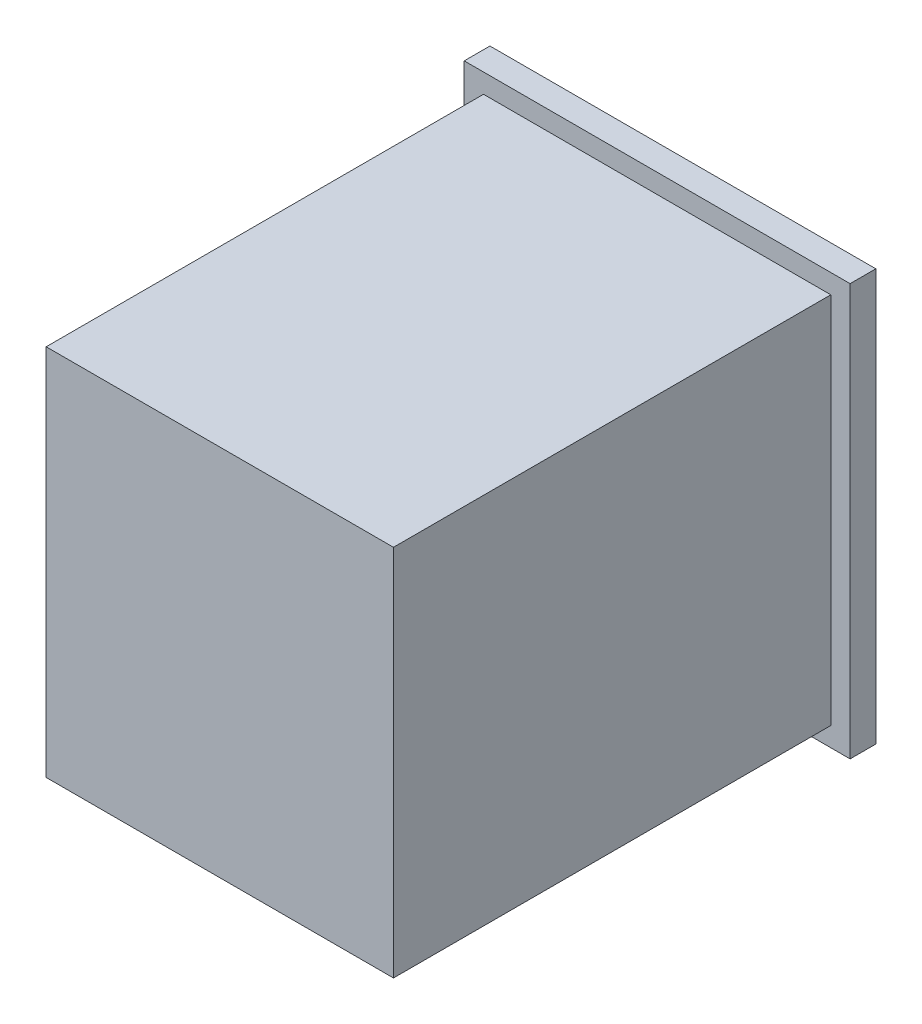
SolidWorks part; units mm, degrees
ref_plane "Front Plane" through (0, 0, 0) normal (0, 0, 1) x (1, 0, 0)
ref_plane "Top Plane" through (0, 0, 0) normal (0, 1, 0) x (1, 0, 0)
ref_plane "Right Plane" through (0, 0, 0) normal (1, 0, 0) x (0, 0, -1)
sketch "Sketch1" plane through (0, 0, 0) normal (0, 0, 1) x (1, 0, 0)
  line L1 (-6.75, -7.25) -> (6.75, -7.25)
  line L2 (-6.75, -7.25) -> (-6.75, 7.25)
  line L3 (-6.75, 7.25) -> (6.75, 7.25)
  line L4 (6.75, -7.25) -> (6.75, 7.25)
  line L5 (-6.75, -7.25) -> (6.75, 7.25) construction
  line L6 (-6.75, 7.25) -> (6.75, -7.25) construction
  point P0 (0, 0)
  dimension "D1" = 13.5
  dimension "D2" = 14.5
extrude "Boss-Extrude1" add sketch "Sketch1" along normal blind 17
sketch "Sketch2" plane through (0, 0, 0) normal (0, 0, 1) x (1, 0, 0)
  line L1 (7.5, -8) -> (-7.5, -8)
  line L2 (7.5, -8) -> (7.5, 8)
  line L3 (7.5, 8) -> (-7.5, 8)
  line L4 (-7.5, -8) -> (-7.5, 8)
  line L5 (7.5, -8) -> (-7.5, 8) construction
  line L6 (7.5, 8) -> (-7.5, -8) construction
  point P0 (0, 0)
  dimension "D1" = 15
  dimension "D2" = 16
extrude "Boss-Extrude2" add sketch "Sketch2" against normal blind 1
sketch "Sketch3" plane through (0, 0, -1) normal (0, 0, -1) x (-1, 0, 0)
  line L0 (-7.5, 0) -> (7.5, 0) construction
  line L1 (-7.5, -8) -> (-7.5, 8) construction
  line L2 (7.5, 8) -> (7.5, -8) construction
  line L3 (0, 8) -> (0, -8) construction
  line L4 (-7.5, 8) -> (7.5, 8) construction
  line L5 (7.5, -8) -> (-7.5, -8) construction
  line L6 (-6, -1.75) -> (6, -6.25) construction
  line L7 (-6, 6.25) -> (6, 6.25)
  line L8 (-6, 6.25) -> (-6, 1.75)
  line L9 (-6, 1.75) -> (6, 1.75)
  line L10 (6, 6.25) -> (6, 1.75)
  line L11 (-6, 6.25) -> (6, 1.75) construction
  line L12 (-6, 1.75) -> (6, 6.25) construction
  line L13 (-6, -6.25) -> (6, -1.75) construction
  line L14 (6, -6.25) -> (6, -1.75)
  line L15 (-6, -1.75) -> (6, -1.75)
  line L16 (-6, -6.25) -> (-6, -1.75)
  line L17 (-6, -6.25) -> (6, -6.25)
  point P12 (0, 4)
  point P21 (0, -4)
  dimension "D1" = 4.5
  dimension "D2" = 12
  dimension "D3" = 1.75
extrude "Cut-Extrude1" cut sketch "Sketch3" against normal blind 10
